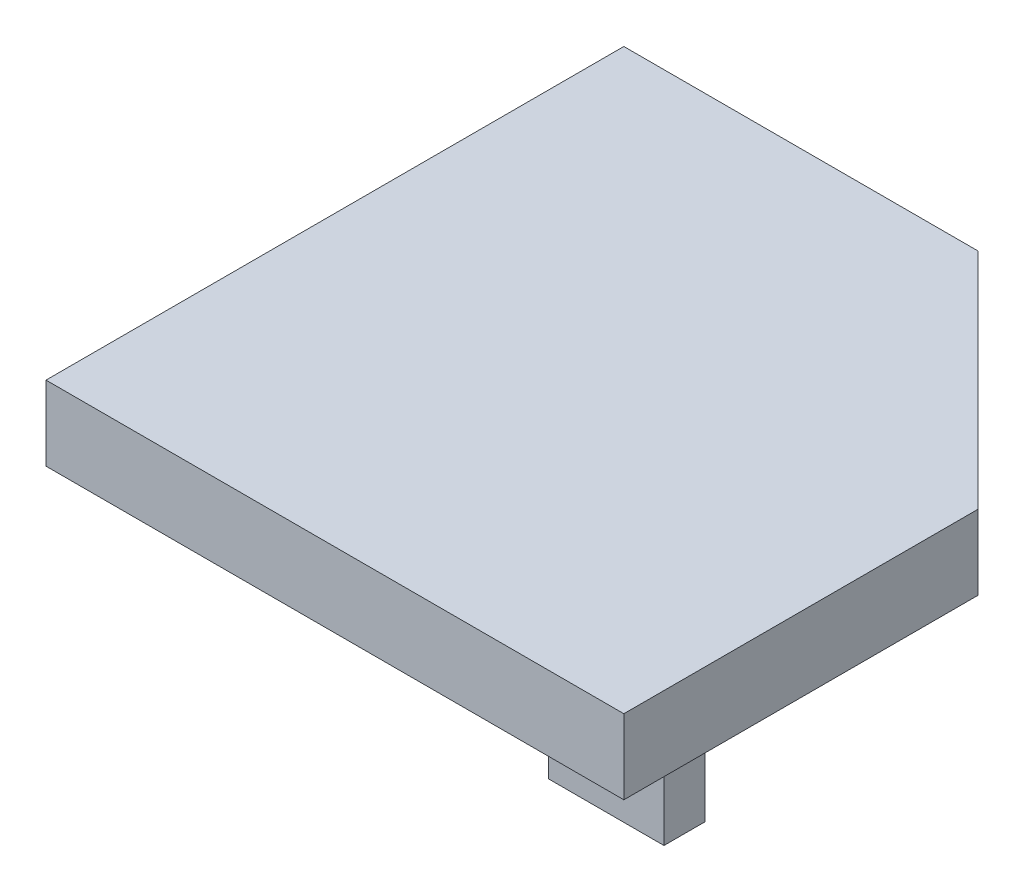
SolidWorks part; units mm, degrees
ref_plane "Front Plane" through (0, 0, 0) normal (0, 0, 1) x (1, 0, 0)
ref_plane "Top Plane" through (0, 0, 0) normal (0, 1, 0) x (1, 0, 0)
ref_plane "Right Plane" through (0, 0, 0) normal (1, 0, 0) x (0, 0, -1)
sketch "Sketch1" plane through (0, 0, 0) normal (0, 1, 0) x (1, 0, 0)
  line L1 (-9.8425, -9.8425) -> (9.8425, -9.8425)
  line L2 (-9.8425, -9.8425) -> (-9.8425, 9.8425)
  line L3 (-9.8425, 9.8425) -> (9.8425, 9.8425)
  line L4 (9.8425, -9.8425) -> (9.8425, 9.8425)
  line L5 (-9.8425, -9.8425) -> (9.8425, 9.8425) construction
  line L6 (-9.8425, 9.8425) -> (9.8425, -9.8425) construction
  point P0 (0, 0)
  dimension "D1" = 19.685
  dimension "D2" = 19.685
extrude "Boss-Extrude1" add sketch "Sketch1" along normal blind 2.54
sketch "Sketch2" plane through (0, 2.54, 0) normal (0, 1, 0) x (1, 0, 0)
  line L0 (-9.8425, 9.8425) -> (-1.4605, 9.8425) construction
  line L1 (9.8425, 9.8425) -> (-9.8425, 9.8425) construction
  line L2 (9.8425, -9.8425) -> (9.8425, 0) construction
  line L3 (9.8425, -9.8425) -> (9.8425, 9.8425) construction
  dimension "D1" = 8.382
sketch "Sketch3" plane through (0, 0, 0) normal (0, -1, 0) x (1, 0, 0)
  line L0 (-9.8425, -9.8425) -> (-1.4605, -9.8425) construction
  line L1 (9.8425, 0) -> (9.8425, 9.8425) construction
  line L2 (-1.4605, -9.8425) -> (-1.4605, 0) construction
  line L3 (-1.4605, 0) -> (9.8425, 0) construction
  line L4 (-4.9848, 9.8425) -> (-4.9847, -9.8425) construction
  line L6 (9.8425, 5.2375) -> (-9.8425, 5.2375) construction
  line L7 (-9.8425, -9.8425) -> (-9.8425, 9.8425) construction
  line L8 (-9.8425, 9.8425) -> (9.8425, 9.8425) construction
  line L14 (-5.6832, -7.0485) -> (-4.2862, -7.0485)
  line L19 (3.3655, 4.539) -> (7.3025, 4.539)
  line L20 (3.3655, 4.539) -> (3.3655, 5.936)
  line L21 (-5.6832, -7.0485) -> (-5.6832, -3.1115)
  line L22 (-5.6832, -3.1115) -> (-4.2862, -3.1115)
  line L23 (-4.2862, -7.0485) -> (-4.2862, -3.1115)
  line L24 (-5.6832, -7.0485) -> (-4.2862, -3.1115) construction
  line L25 (-5.6832, -3.1115) -> (-4.2862, -7.0485) construction
  line L26 (3.3655, 5.936) -> (7.3025, 5.936)
  line L27 (7.3025, 4.539) -> (7.3025, 5.936)
  line L28 (3.3655, 4.539) -> (7.3025, 5.936) construction
  line L29 (3.3655, 5.936) -> (7.3025, 4.539) construction
  point P17 (-4.9847, -5.08)
  point P22 (5.334, 5.2375)
  dimension "D1" = 4.8578
  dimension "D4" = 4.605
  dimension "D5" = 3.937
  dimension "D6" = 1.397
  dimension "D7" = 2.794
  dimension "D8" = 2.54
extrude "Boss-Extrude2" add sketch "Sketch3" along normal blind 4.572
chamfer "Chamfer1" distance 7.62 angle 45 1 edges at (9.8425, 1.27, -9.8425)
